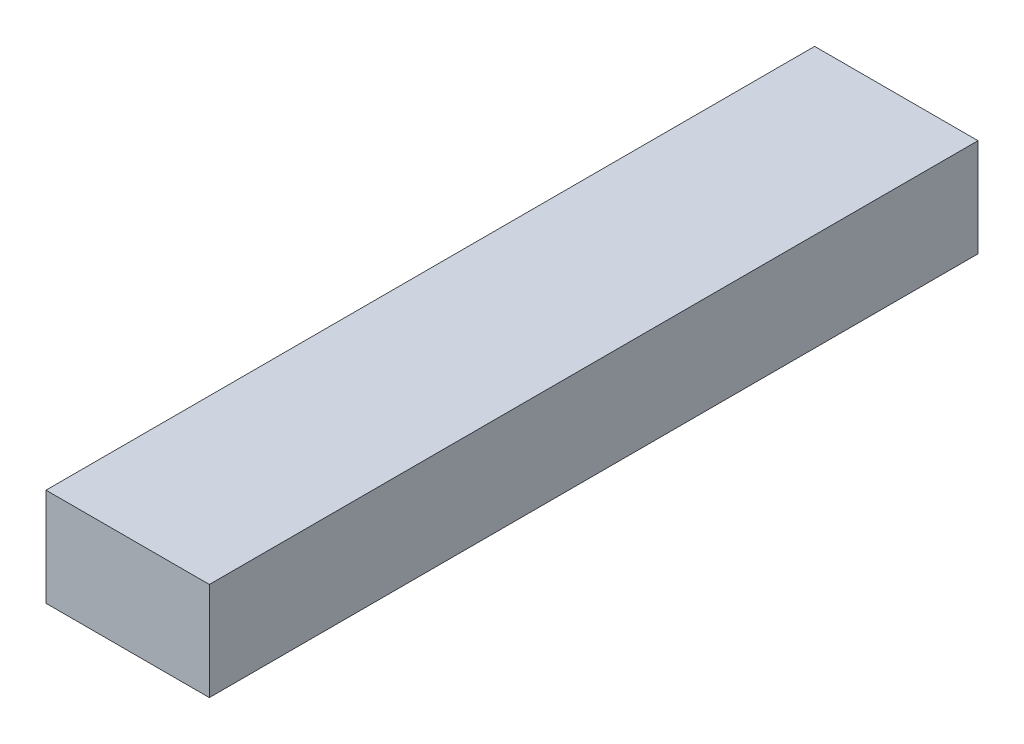
SolidWorks part; units mm, degrees
ref_plane "Front" through (0, 0, 0) normal (0, 0, 1) x (1, 0, 0)
ref_plane "Top" through (0, 0, 0) normal (0, 1, 0) x (1, 0, 0)
ref_plane "Right" through (0, 0, 0) normal (1, 0, 0) x (0, 0, -1)
sketch "Sketch1" plane through (0, 0, 0) normal (0, 0, 1) x (1, 0, 0)
  line L1 (0, 0) -> (63.5, 0)
  line L2 (0, 0) -> (0, 38.1)
  line L3 (0, 38.1) -> (63.5, 38.1)
  line L4 (63.5, 0) -> (63.5, 38.1)
  dimension "D1" = 63.5
  dimension "D2" = 38.1
extrude "Boss-Extrude1" add sketch "Sketch1" against normal blind 298.8
